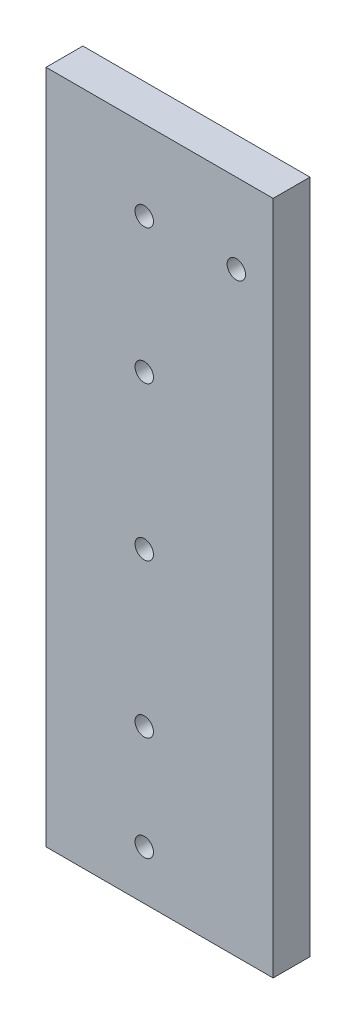
SolidWorks part; units mm, degrees
ref_plane "前视基准面" through (0, 0, 0) normal (0, 0, 1) x (1, 0, 0)
ref_plane "上视基准面" through (0, 0, 0) normal (0, 1, 0) x (1, 0, 0)
ref_plane "右视基准面" through (0, 0, 0) normal (1, 0, 0) x (0, 0, -1)
other "Configuration Table"
sketch "草图1" plane through (0, 0, 0) normal (0, 0, 1) x (1, 0, 0)
  line L1 (-92.5, -275) -> (92.5, -275)
  line L2 (-92.5, -275) -> (-92.5, 275)
  line L3 (-92.5, 275) -> (92.5, 275)
  line L4 (92.5, -275) -> (92.5, 275)
  line L5 (-92.5, -275) -> (92.5, 275) construction
  line L6 (-92.5, 275) -> (92.5, -275) construction
  circle A0 centre (62.5, 210) radius 7.5
  circle A1 centre (-12.5, 210) radius 7.5
  circle A2 centre (-12.5, -235) radius 7.5
  circle A3 centre (-12.5, -150) radius 7.5
  circle A5 centre (-12.5, -25) radius 7.5
  circle A7 centre (-12.5, 100) radius 7.5
  point P0 (0, 0)
  dimension "D2" = 15
  dimension "D6" = 15
  dimension "D11" = 80
  dimension "D3" = 30
  dimension "D4" = 65
  dimension "D5" = 40
  dimension "D7" = 85
  dimension "D8" = 110
  dimension "D9" = 125
  dimension "D10" = 125
  dimension "D12" = 75
extrude "凸台-拉伸1" add sketch "草图1" along normal blind 30
